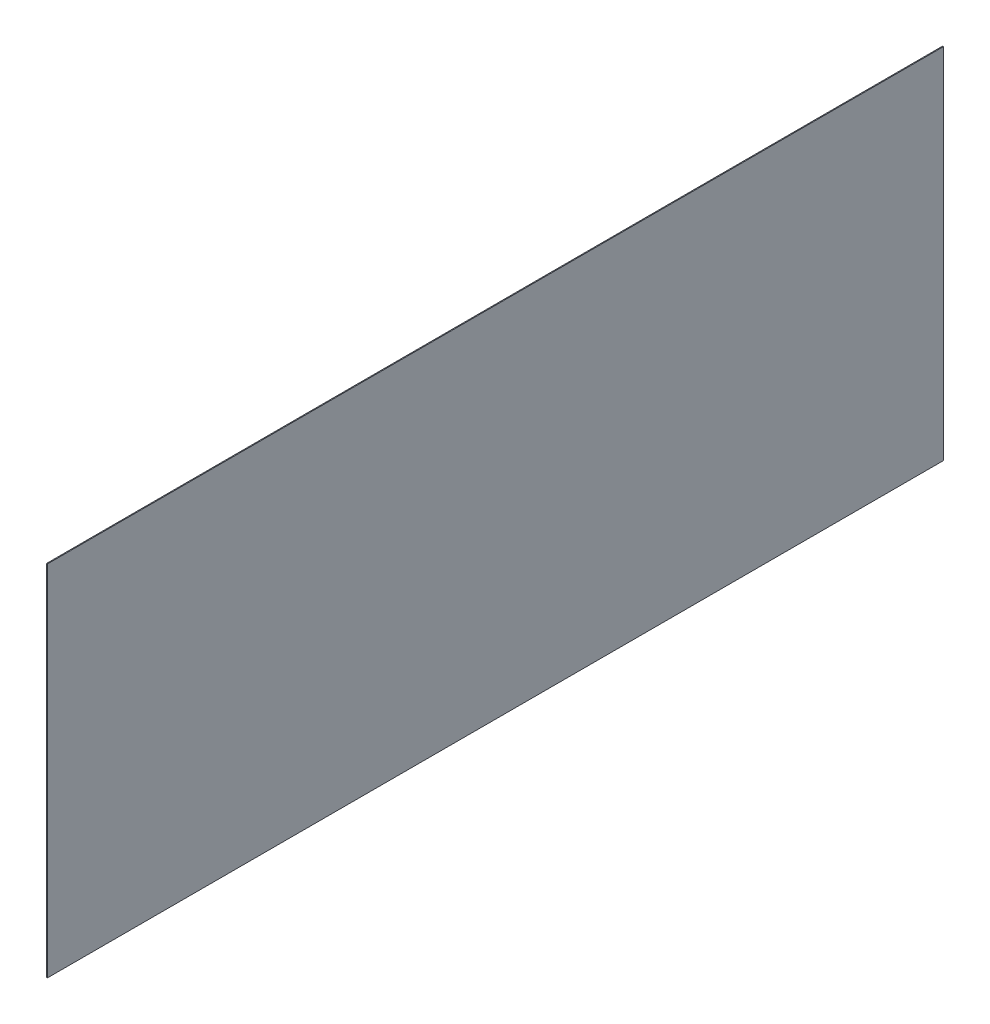
SolidWorks part; units mm, degrees
ref_plane "Front Plane" through (0, 0, 0) normal (0, 0, 1) x (1, 0, 0)
ref_plane "Top Plane" through (0, 0, 0) normal (0, 1, 0) x (1, 0, 0)
ref_plane "Right Plane" through (0, 0, 0) normal (1, 0, 0) x (0, 0, -1)
sketch "Croquis1" plane through (0, 0, 0) normal (1, 0, 0) x (0, 0, -1)
  line L1 (0, 0) -> (100, 0)
  line L2 (0, 0) -> (0, 40)
  line L3 (0, 40) -> (100, 40)
  line L4 (100, 0) -> (100, 40)
  dimension "D1" = 100
  dimension "D2" = 40
extrude "Saliente-Extruir1" add sketch "Croquis1" along normal blind 0.1
sketch "Croquis5"
